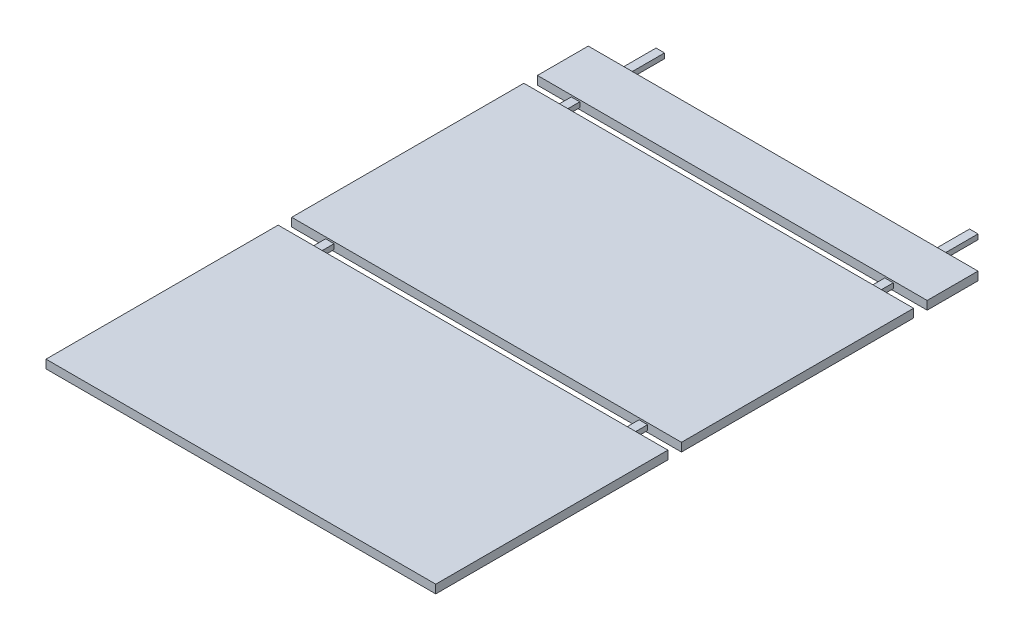
SolidWorks part; units mm, degrees
ref_plane "Piano frontale" through (0, 0, 0) normal (0, 0, 1) x (1, 0, 0)
ref_plane "Piano superiore" through (0, 0, 0) normal (0, 1, 0) x (1, 0, 0)
ref_plane "Piano destro" through (0, 0, 0) normal (1, 0, 0) x (0, 0, -1)
sketch "Schizzo1" plane through (0, 0, 0) normal (0, 0, 1) x (1, 0, 0)
  line L1 (-1150, -25) -> (1150, -25)
  line L2 (-1150, -25) -> (-1150, 25)
  line L3 (-1150, 25) -> (1150, 25)
  line L4 (1150, -25) -> (1150, 25)
  line L5 (-1150, -25) -> (1150, 25) construction
  line L6 (-1150, 25) -> (1150, -25) construction
  point P0 (0, 0)
  dimension "D1" = 50
  dimension "D2" = 2300
extrude "Estrusione-Estrusione1" add sketch "Schizzo1" along normal blind 3400
sketch "Schizzo2" plane through (0, 25, 0) normal (0, 1, 0) x (1, 0, 0)
  line L0 (-1150, -3400) -> (-1150, 0) construction
  line L1 (-1150, -2030) -> (-950, -2030)
  line L2 (-1150, -2030) -> (-1150, -1950)
  line L3 (-1150, -1950) -> (-950, -1950)
  line L4 (1150, -2030) -> (1150, -1950)
  line L5 (1150, -3400) -> (1150, 0) construction
  line L6 (1150, 0) -> (-1150, 0) construction
  line L7 (-1150, -580) -> (-950, -580)
  line L8 (-1150, -580) -> (-1150, -500)
  line L9 (-1150, -500) -> (-950, -500)
  line L10 (1150, -580) -> (1150, -500)
  line L11 (-1150, -200) -> (-950, -200)
  line L12 (-1150, -200) -> (-1150, 0)
  line L13 (-1150, 0) -> (-950, 0)
  line L14 (-950, -200) -> (-950, 0)
  line L15 (-950, -200) -> (-900, -200) construction
  line L16 (1150, -200) -> (950, -200)
  line L17 (1150, -200) -> (1150, 0)
  line L18 (1150, 0) -> (950, 0)
  line L19 (950, -200) -> (950, 0)
  line L20 (-900, 0) -> (900, 0)
  line L21 (-900, 0) -> (-900, -200)
  line L22 (-900, -200) -> (900, -200)
  line L23 (900, 0) -> (900, -200)
  line L24 (900, -200) -> (950, -200) construction
  line L25 (-1150, -3400) -> (-1150, -2030) construction
  line L26 (-1150, -1950) -> (-1150, -580) construction
  line L27 (-1150, -500) -> (-1150, -200) construction
  line L28 (-950, -2030) -> (-950, -1950)
  line L29 (-900, -2030) -> (-900, -1950)
  line L30 (-950, -580) -> (-950, -500)
  line L31 (-900, -580) -> (-900, -500)
  line L32 (900, -2030) -> (900, -1950)
  line L33 (950, -2030) -> (950, -1950)
  line L34 (900, -580) -> (900, -500)
  line L35 (950, -580) -> (950, -500)
  line L36 (-900, -2030) -> (900, -2030)
  line L37 (-900, -1950) -> (900, -1950)
  line L38 (-900, -580) -> (900, -580)
  line L39 (-900, -500) -> (900, -500)
  line L40 (950, -580) -> (1150, -580)
  line L41 (950, -500) -> (1150, -500)
  line L42 (950, -1950) -> (1150, -1950)
  line L43 (950, -2030) -> (1150, -2030)
  line L44 (-950, -2030) -> (-900, -2030) construction
  line L45 (900, -2030) -> (950, -2030) construction
  line L46 (900, -500) -> (950, -500) construction
  line L47 (-950, -500) -> (-900, -500) construction
  line L48 (-1150, -1990) -> (-950, -1990) construction
  line L49 (1150, -1990) -> (950, -1990) construction
  line L50 (-1150, -540) -> (-950, -540) construction
  line L51 (1150, -540) -> (950, -540) construction
  dimension "D1" = 80
  dimension "D2" = 200
  dimension "D3" = 1800
  dimension "D4" = 200
  dimension "D5" = 200
  dimension "D6" = 50
  dimension "D7" = 300
extrude "Taglio-Estrusione1" cut sketch "Schizzo2" against normal through all
sketch "Schizzo3" plane through (1150, 0, 0) normal (1, 0, 0) x (0, 0, -1)
  line L0 (-1950, -25) -> (-1950, 25) construction
  line L1 (-2030, 25) -> (-1950, 25)
  line L2 (-2030, 25) -> (-2030, 15)
  line L3 (-2030, 15) -> (-1950, 15)
  line L4 (-1950, 25) -> (-1950, 15)
  line L5 (-2030, -25) -> (-2030, 25) construction
  line L6 (-1950, -25) -> (-2030, -25)
  line L7 (-1950, -25) -> (-1950, -15)
  line L8 (-1950, -15) -> (-2030, -15)
  line L9 (-2030, -25) -> (-2030, -15)
  line L10 (-500, -25) -> (-500, 25) construction
  line L11 (-580, 25) -> (-500, 25)
  line L12 (-580, 25) -> (-580, 15)
  line L13 (-580, 15) -> (-500, 15)
  line L14 (-500, 25) -> (-500, 15)
  line L15 (-580, -25) -> (-580, 25) construction
  line L16 (-500, -25) -> (-580, -25)
  line L17 (-500, -25) -> (-500, -15)
  line L18 (-500, -15) -> (-580, -15)
  line L19 (-580, -25) -> (-580, -15)
  line L20 (0, -25) -> (0, 25) construction
  line L21 (-200, 25) -> (0, 25)
  line L22 (-200, 25) -> (-200, 15)
  line L23 (-200, 15) -> (0, 15)
  line L24 (0, 25) -> (0, 15)
  line L25 (-200, -25) -> (-200, 25) construction
  line L26 (0, -25) -> (-200, -25)
  line L27 (0, -25) -> (0, -15)
  line L28 (0, -15) -> (-200, -15)
  line L29 (-200, -25) -> (-200, -15)
  dimension "D1" = 10
extrude "Taglio-Estrusione2" cut sketch "Schizzo3" against normal through all
